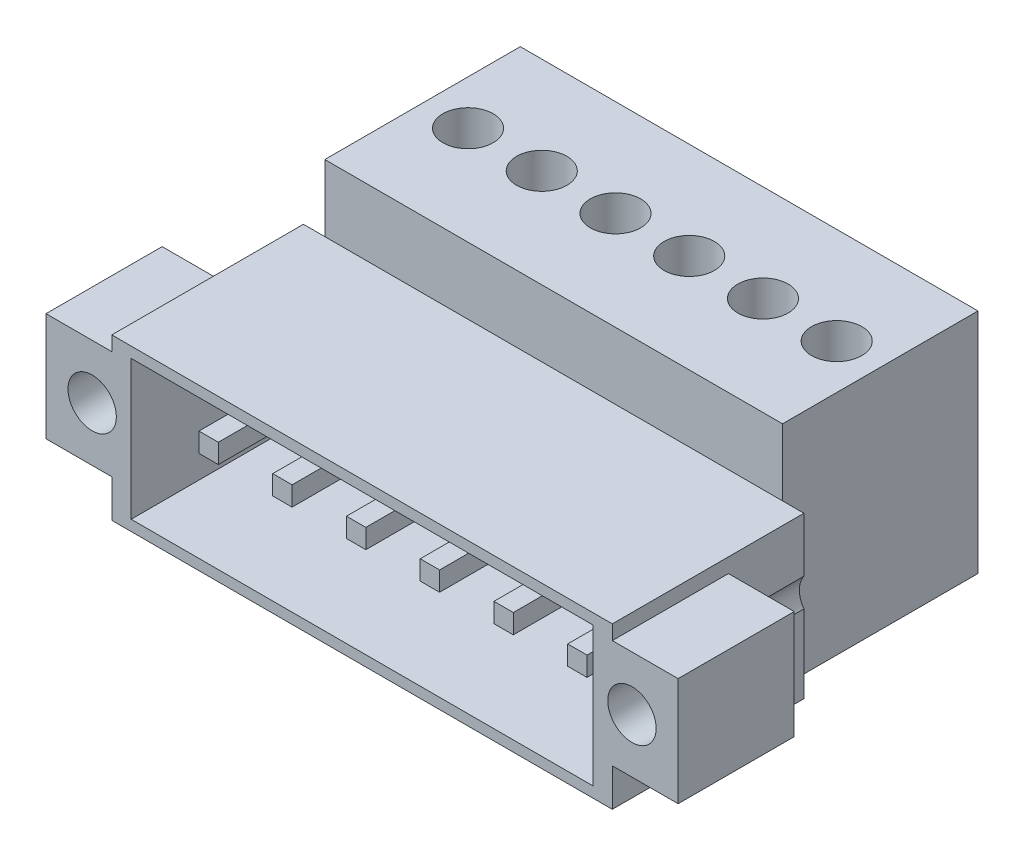
SolidWorks part; units mm, degrees
material "Nylon 101"
ref_plane "Front Plane" through (0, 0, 0) normal (0, 0, 1) x (1, 0, 0)
ref_plane "Top Plane" through (0, 0, 0) normal (0, 1, 0) x (1, 0, 0)
ref_plane "Right Plane" through (0, 0, 0) normal (1, 0, 0) x (0, 0, -1)
ref_plane "PL mating face" through (0, 0, 3) normal (0, 0, 1) x (1, 0, 0)
sketch "SK Shroud" plane through (0, 0, 3) normal (0, 0, 1) x (1, 0, 0)
  line L0 (-12.93, -4.75) -> (12.93, -4.75)
  line L1 (12.93, -4.75) -> (12.93, 3.55)
  line L2 (12.93, 3.55) -> (-12.93, 3.55)
  line L3 (-12.93, 3.55) -> (-12.93, -4.75)
extrude "Shroud" add sketch "SK Shroud" against normal blind 9.9
sketch "SK Flange ears" plane through (0, 0, 3) normal (0, 0, 1) x (1, 0, 0)
  line L0 (12.93, -2.8) -> (16.33, -2.8)
  line L1 (16.33, -2.8) -> (16.33, 2.8)
  line L2 (16.33, 2.8) -> (12.93, 2.8)
  line L3 (12.93, 2.8) -> (12.93, -2.8)
  line L4 (-16.33, -2.8) -> (-12.93, -2.8)
  line L5 (-12.93, -2.8) -> (-12.93, 2.8)
  line L6 (-12.93, 2.8) -> (-16.33, 2.8)
  line L7 (-16.33, 2.8) -> (-16.33, -2.8)
extrude "Flange ears" add sketch "SK Flange ears" against normal blind 6
sketch "SK Cavity" plane through (0, 0, 3) normal (0, 0, 1) x (1, 0, 0)
  line L0 (-11.93, -4.2) -> (11.93, -4.2)
  line L1 (11.93, -4.2) -> (11.93, 3)
  line L2 (11.93, 3) -> (-11.93, 3)
  line L3 (-11.93, 3) -> (-11.93, -4.2)
extrude "Cavity" cut sketch "SK Cavity" against normal blind 7.6
ref_plane "PL shroud rear" through (0, 0, -6.9) normal (0, 0, 1) x (1, 0, 0)
sketch "SK Terminal block" plane through (0, 0, -6.9) normal (0, 0, 1) x (1, 0, 0)
  line L0 (-11.825, -4.75) -> (11.825, -4.75)
  line L1 (11.825, -4.75) -> (11.825, 7)
  line L2 (11.825, 7) -> (-11.825, 7)
  line L3 (-11.825, 7) -> (-11.825, -4.75)
extrude "Terminal block" add sketch "SK Terminal block" against normal blind 10.1
sketch "SK Insert holes" plane through (0, 0, 0) normal (0, 0, 1) x (1, 0, 0)
  circle A0 centre (-13.945, 0) radius 1.25
  circle A1 centre (13.945, 0) radius 1.25
extrude "Insert holes" cut sketch "SK Insert holes" against normal through all and the other way through all
ref_plane "PL cavity floor" through (0, 0, -4.6) normal (0, 0, 1) x (1, 0, 0)
sketch "SK Contact pins" plane through (0, 0, -4.6) normal (0, 0, 1) x (1, 0, 0)
  line L0 (-10.025, -1.1) -> (-9.025, -1.1)
  line L1 (-9.025, -1.1) -> (-9.025, -0.1)
  line L2 (-9.025, -0.1) -> (-10.025, -0.1)
  line L3 (-10.025, -0.1) -> (-10.025, -1.1)
  line L4 (-6.215, -1.1) -> (-5.215, -1.1)
  line L5 (-5.215, -1.1) -> (-5.215, -0.1)
  line L6 (-5.215, -0.1) -> (-6.215, -0.1)
  line L7 (-6.215, -0.1) -> (-6.215, -1.1)
  line L8 (-2.405, -1.1) -> (-1.405, -1.1)
  line L9 (-1.405, -1.1) -> (-1.405, -0.1)
  line L10 (-1.405, -0.1) -> (-2.405, -0.1)
  line L11 (-2.405, -0.1) -> (-2.405, -1.1)
  line L12 (1.405, -1.1) -> (2.405, -1.1)
  line L13 (2.405, -1.1) -> (2.405, -0.1)
  line L14 (2.405, -0.1) -> (1.405, -0.1)
  line L15 (1.405, -0.1) -> (1.405, -1.1)
  line L16 (5.215, -1.1) -> (6.215, -1.1)
  line L17 (6.215, -1.1) -> (6.215, -0.1)
  line L18 (6.215, -0.1) -> (5.215, -0.1)
  line L19 (5.215, -0.1) -> (5.215, -1.1)
  line L20 (9.025, -1.1) -> (10.025, -1.1)
  line L21 (10.025, -1.1) -> (10.025, -0.1)
  line L22 (10.025, -0.1) -> (9.025, -0.1)
  line L23 (9.025, -0.1) -> (9.025, -1.1)
extrude "Contact pins" add sketch "SK Contact pins" along normal blind 6
ref_plane "PL wire face" through (0, 0, -17) normal (0, 0, 1) x (1, 0, 0)
sketch "SK Wire entries" plane through (0, 0, -17) normal (0, 0, 1) x (1, 0, 0)
  line L0 (-10.825, -3.4) -> (-8.225, -3.4)
  line L1 (-8.225, -3.4) -> (-8.225, -0.6)
  line L2 (-8.225, -0.6) -> (-10.825, -0.6)
  line L3 (-10.825, -0.6) -> (-10.825, -3.4)
  line L4 (-7.015, -3.4) -> (-4.415, -3.4)
  line L5 (-4.415, -3.4) -> (-4.415, -0.6)
  line L6 (-4.415, -0.6) -> (-7.015, -0.6)
  line L7 (-7.015, -0.6) -> (-7.015, -3.4)
  line L8 (-3.205, -3.4) -> (-0.605, -3.4)
  line L9 (-0.605, -3.4) -> (-0.605, -0.6)
  line L10 (-0.605, -0.6) -> (-3.205, -0.6)
  line L11 (-3.205, -0.6) -> (-3.205, -3.4)
  line L12 (0.605, -3.4) -> (3.205, -3.4)
  line L13 (3.205, -3.4) -> (3.205, -0.6)
  line L14 (3.205, -0.6) -> (0.605, -0.6)
  line L15 (0.605, -0.6) -> (0.605, -3.4)
  line L16 (4.415, -3.4) -> (7.015, -3.4)
  line L17 (7.015, -3.4) -> (7.015, -0.6)
  line L18 (7.015, -0.6) -> (4.415, -0.6)
  line L19 (4.415, -0.6) -> (4.415, -3.4)
  line L20 (8.225, -3.4) -> (10.825, -3.4)
  line L21 (10.825, -3.4) -> (10.825, -0.6)
  line L22 (10.825, -0.6) -> (8.225, -0.6)
  line L23 (8.225, -0.6) -> (8.225, -3.4)
extrude "Wire entries" cut sketch "SK Wire entries" along normal blind 6
ref_plane "PL top face" through (0, 7, 0) normal (0, 1, 0) x (1, 0, 0)
sketch "SK Clamp screw holes" plane through (0, 7, 0) normal (0, 1, 0) x (1, 0, 0)
  circle A0 centre (-9.525, 12) radius 1.3
  circle A1 centre (-5.715, 12) radius 1.3
  circle A2 centre (-1.905, 12) radius 1.3
  circle A3 centre (1.905, 12) radius 1.3
  circle A4 centre (5.715, 12) radius 1.3
  circle A5 centre (9.525, 12) radius 1.3
extrude "Clamp screw holes" cut sketch "SK Clamp screw holes" against normal blind 3
